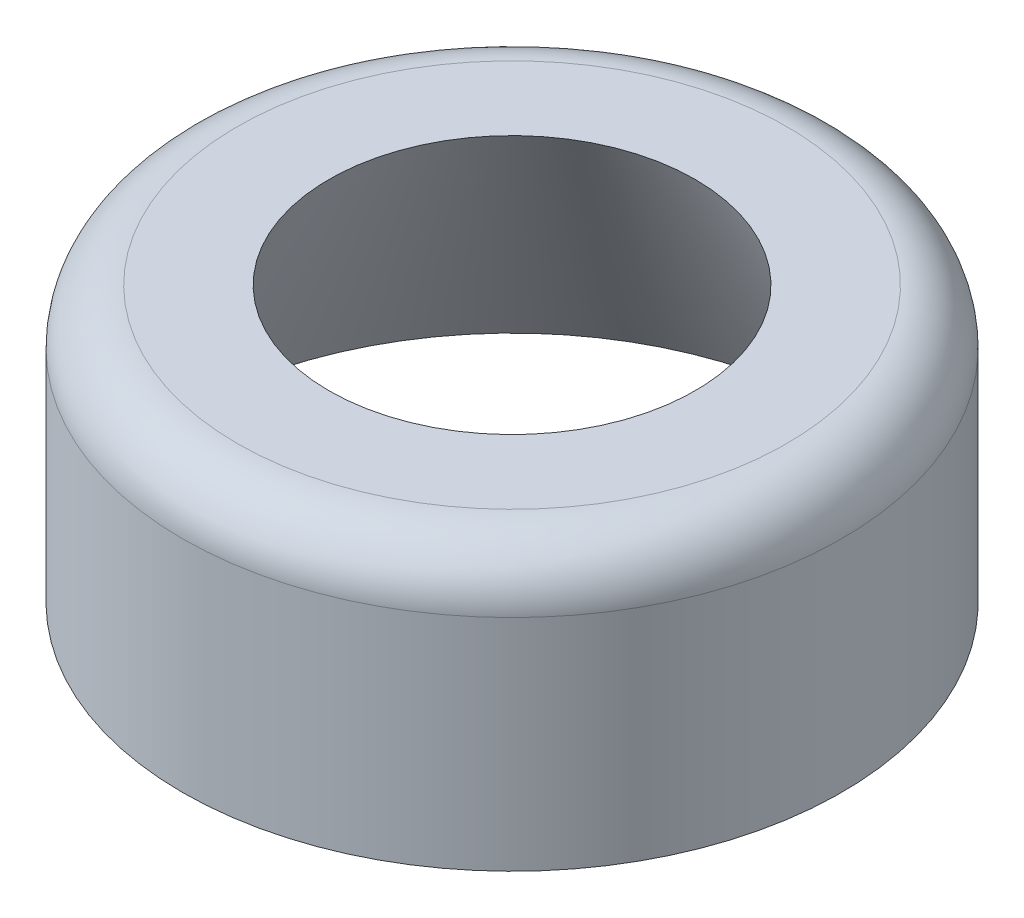
SolidWorks part; units mm, degrees
ref_plane "Front Plane" through (0, 0, 0) normal (0, 0, 1) x (1, 0, 0)
ref_plane "Top Plane" through (0, 0, 0) normal (0, 1, 0) x (1, 0, 0)
ref_plane "Right Plane" through (0, 0, 0) normal (1, 0, 0) x (0, 0, -1)
sketch "Sketch1" plane through (0, 0, 0) normal (0, 0, 1) x (1, 0, 0)
  line L0 (0, 31.8361) -> (0, -33.1276) construction
  line L1 (7.62, 0) -> (10.795, 0)
  line L2 (12.7, -1.905) -> (12.7, -9.525)
  line L3 (7.62, 0) -> (12.7, -9.525)
  arc A0 (12.7, -1.905) -> (10.795, 0) centre (10.795, -1.905) ccw
  point P8 (12.7, 0)
  dimension "D4" = 1.905
  dimension "D1" = 7.62
  dimension "D2" = 9.525
  dimension "D3" = 5.08
revolve "Revolve-Thin1" add sketch "Sketch1" angle 360 about L0
